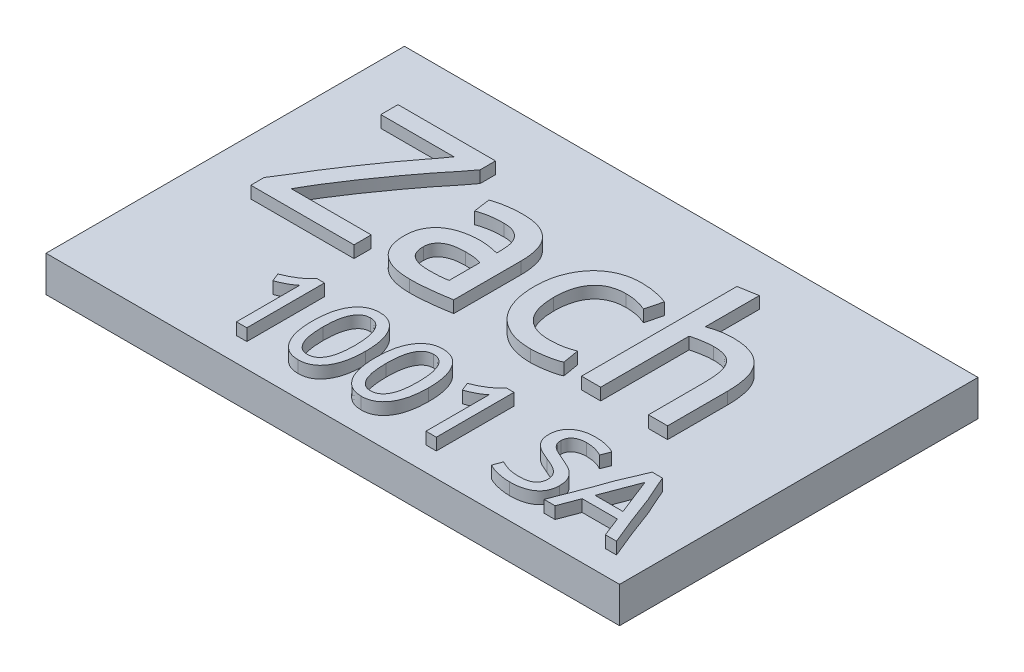
SolidWorks part; units mm, degrees
material "PET"
ref_plane "Front Plane" through (0, 0, 0) normal (0, 0, 1) x (1, 0, 0)
ref_plane "Top Plane" through (0, 0, 0) normal (0, 1, 0) x (1, 0, 0)
ref_plane "Right Plane" through (0, 0, 0) normal (1, 0, 0) x (0, 0, -1)
sketch "Sketch1" plane through (0, 0, 0) normal (0, 1, 0) x (1, 0, 0)
  line L1 (-24, -15) -> (24, -15)
  line L2 (-24, -15) -> (-24, 15)
  line L3 (-24, 15) -> (24, 15)
  line L4 (24, -15) -> (24, 15)
  line L5 (-24, -15) -> (24, 15) construction
  line L6 (-24, 15) -> (24, -15) construction
  point P0 (0, 0)
  dimension "D1" = 48
  dimension "D2" = 30
extrude "Boss-Extrude1" add sketch "Sketch1" along normal blind 3
sketch "Sketch2" plane through (0, 3, 0) normal (0, 1, 0) x (1, 0, 0)
  line L0 (-24, -13) -> (24, -13) construction
  line L1 (-24, 15) -> (-24, -15) construction
  line L2 (24, -15) -> (24, 15) construction
  text T0 "1001 SA " font "Ubuntu" height 6.5
  dimension "D1" = 2
extrude "Boss-Extrude2" add sketch "Sketch2" along normal blind 1
sketch "Sketch3" plane through (0, 3, 0) normal (0, 1, 0) x (1, 0, 0)
  line L0 (-24, -2.5) -> (24, -2.5) construction
  line L1 (-24, 15) -> (-24, -15) construction
  line L2 (24, -15) -> (24, 15) construction
  line L3 (-24, -15) -> (24, -15) construction
  text T0 " Zach" font "Ubuntu" height 12
  dimension "D1" = 12.5
extrude "Boss-Extrude3" add sketch "Sketch3" along normal blind 1
sketch "Sketch4" plane through (0, 0, 0) normal (0, -1, 0) x (1, 0, 0)
  line L0 (-24, -15) -> (24, 15) construction
  line L1 (-24, 15) -> (24, -15) construction
  line L3 (-23, 7) -> (23, 7)
  line L4 (-23, 7) -> (-23, -7)
  line L5 (-23, -7) -> (23, -7)
  line L6 (23, 7) -> (23, -7)
  line L7 (-23, 7) -> (23, -7) construction
  line L8 (-23, -7) -> (23, 7) construction
  point P8 (0, 0)
  dimension "D1" = 14
  dimension "D2" = 46
extrude "Cut-Extrude1" cut sketch "Sketch4" against normal blind 1
sketch "Sketch5" [suppressed] plane through (0, 3, 0) normal (0, 1, 0) x (1, 0, 0)
  line L0 (-25, 15) -> (-25, 5)
  line L1 (-25, 15) -> (-25, -15) construction
  dimension "D1" = 12
